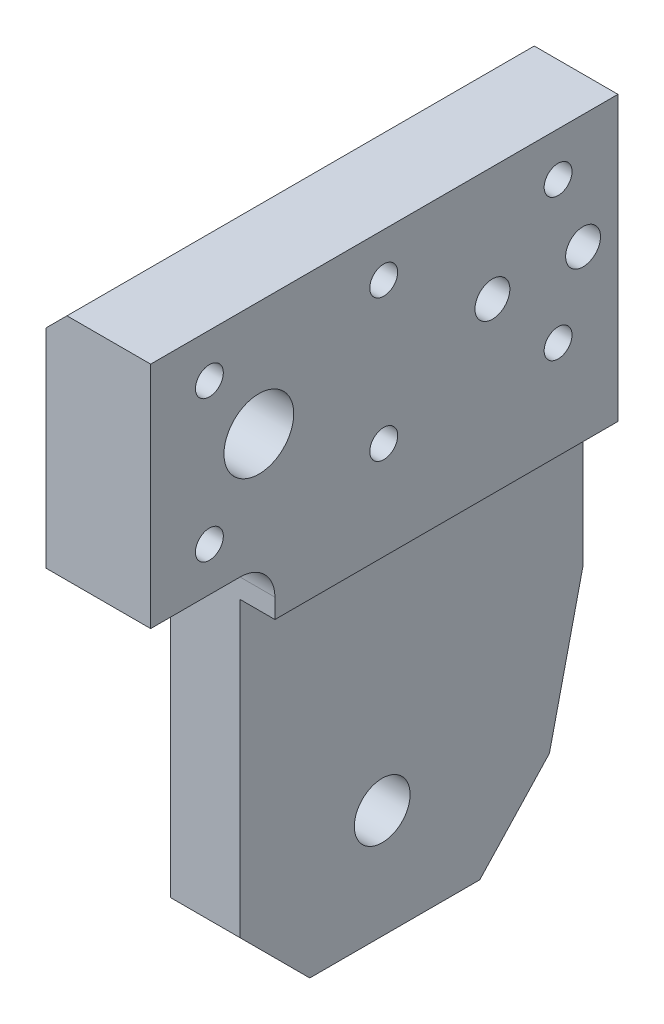
SolidWorks part; units mm, degrees
ref_plane "Спереди" through (0, 0, 0) normal (0, 0, 1) x (1, 0, 0)
ref_plane "Сверху" through (0, 0, 0) normal (0, 1, 0) x (1, 0, 0)
ref_plane "Справа" through (0, 0, 0) normal (1, 0, 0) x (0, 0, -1)
sketch "Эскиз1" plane through (0, 0, 0) normal (1, 0, 0) x (0, 0, -1)
  line L0 (-24.4184, -32.65) -> (-6.6022, -32.65)
  line L1 (-24.4184, 0.1951) -> (42.5816, 0.1951)
  line L2 (-6.6022, -92.4427) -> (35.2885, -92.4427)
  line L3 (-6.6022, -92.4427) -> (-6.6022, -32.65)
  line L4 (42.5816, 0.1951) -> (42.5816, -60.8317)
  line L5 (42.5816, -60.8317) -> (35.2885, -92.4427)
  line L10 (-24.4184, -32.65) -> (-24.4184, 0.1951)
  circle A6 centre (13.7842, -76.834) radius 4
extrude "Вытянуть1" add sketch "Эскиз1" against normal blind 15
sketch "Эскиз2" plane through (0, 0, 0) normal (0, 0, 1) x (1, 0, 0)
  line L1 (1.4632, -40.4274) -> (-5.0044, -40.4274)
  line L2 (1.4632, -40.4274) -> (1.4632, -103.053)
  line L3 (1.4632, -103.053) -> (-5.0044, -103.053)
  line L4 (-5.0044, -40.4274) -> (-5.0044, -103.053)
extrude "Вырез-Вытянуть1" cut sketch "Эскиз2" against normal mid plane 110
sketch "Эскиз3" plane through (-15, 0, 0) normal (-1, 0, 0) x (0, 0, 1)
  circle A0 centre (8.9047, -16.2275) radius 5
  circle A1 centre (-37.5816, -16.2275) radius 2.5
  circle A2 centre (-24.5816, -16.2275) radius 2.5
extrude "Вырез-Вытянуть2" cut sketch "Эскиз3" against normal through all
chamfer "Фаска1" distance 10 angle 45 1 edges at (-10.0022, -92.4427, 6.6022)
chamfer "Фаска2" distance 11 angle 30 1 edges at (-10.0022, -92.4427, -35.2885)
fillet "Скругление1" radius 5 1 edges at (-7.5, -32.65, 6.6022)
sketch "Эскиз4" plane through (-15, 0, 0) normal (-1, 0, 0) x (0, 0, 1)
  circle A0 centre (-34, -6.0808) radius 2
  circle A1 centre (-9, -6.0808) radius 2
  circle A2 centre (16, -6.0808) radius 2
  circle A3 centre (16, -26.3741) radius 2
  circle A4 centre (-9, -26.3741) radius 2
  circle A5 centre (-34, -26.3741) radius 2
extrude "Вырез-Вытянуть3" cut sketch "Эскиз4" against normal through all
sketch "Эскиз5" plane through (-15, 0, 0) normal (-1, 0, 0) x (0, 0, 1)
  circle A0 centre (-34, -6.0808) radius 3
  circle A1 centre (-9, -6.0808) radius 3
  circle A2 centre (16, -6.0808) radius 3
  circle A3 centre (16, -26.3741) radius 3
  circle A4 centre (-9, -26.3741) radius 3
  circle A5 centre (-34, -26.3741) radius 3
extrude "Вырез-Вытянуть4" cut sketch "Эскиз5" against normal blind 1.5 draft 33
chamfer "Фаска3" distance 3 angle 45 1 edges at (-15, 0.1951, -9.0816)
